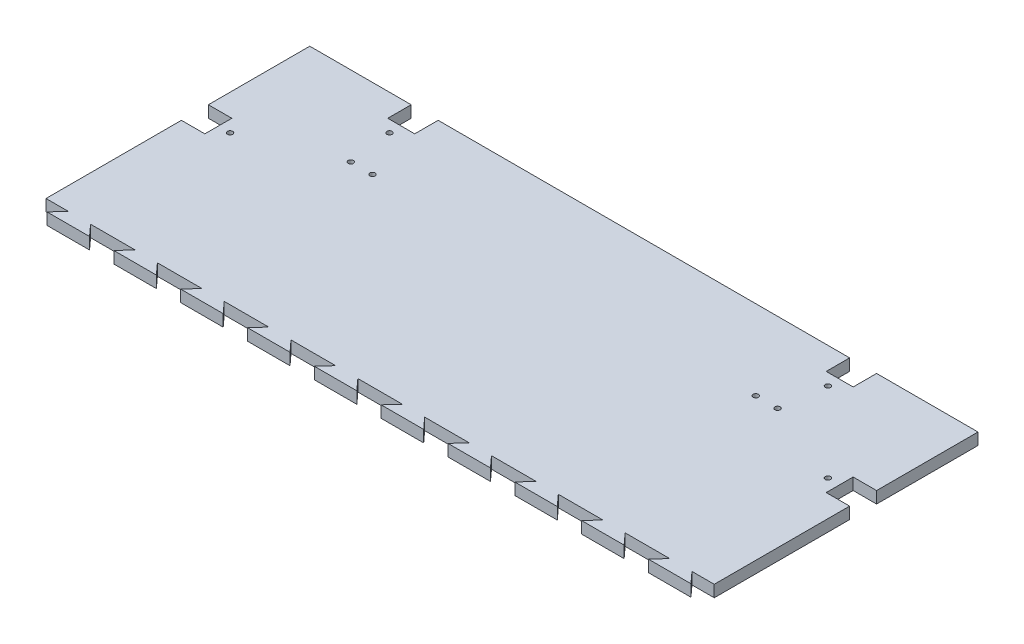
SolidWorks part; units mm, degrees
material "Multistrato di pioppo"
ref_plane "Piano frontale" through (0, 0, 0) normal (0, 0, 1) x (1, 0, 0)
ref_plane "Piano superiore" through (0, 0, 0) normal (0, 1, 0) x (1, 0, 0)
ref_plane "Piano destro" through (0, 0, 0) normal (1, 0, 0) x (0, 0, -1)
sketch "Schizzo1" plane through (0, 0, 0) normal (0, 1, 0) x (1, 0, 0)
  line L1 (0, 0) -> (-570, 0)
  line L2 (0, 0) -> (0, 450)
  line L3 (0, 450) -> (-570, 450)
  line L4 (-570, 0) -> (-570, 450)
  dimension "D1" = 570
  dimension "D2" = 450
extrude "Estrusione-Estrusione1" add sketch "Schizzo1" along normal blind 10
sketch "Schizzo2" plane through (0, 0, 0) normal (0, -1, 0) x (1, 0, 0)
  line L0 (-570, 0) -> (0, 0) construction
  line L1 (-483.5, 0) -> (-460.5, 0)
  line L3 (-483.5, 0) -> (-483.5, -20)
  line L5 (-483.5, -20) -> (-460.5, -20)
  line L6 (-460.5, 0) -> (-460.5, -20)
  line L7 (-483.5, 0) -> (-460.5, -20) construction
  line L8 (-483.5, -20) -> (-460.5, 0) construction
  line L9 (0, 0) -> (0, -450) construction
  line L10 (-109.5, 0) -> (-86.5, 0)
  line L11 (-109.5, 0) -> (-109.5, -20)
  line L12 (-109.5, -20) -> (-86.5, -20)
  line L13 (-86.5, 0) -> (-86.5, -20)
  line L14 (-109.5, 0) -> (-86.5, -20) construction
  line L15 (-109.5, -20) -> (-86.5, 0) construction
  line L16 (0, -86.5) -> (-20, -86.5)
  line L17 (0, -86.5) -> (0, -109.5)
  line L18 (0, -109.5) -> (-20, -109.5)
  line L19 (-20, -86.5) -> (-20, -109.5)
  line L20 (0, -86.5) -> (-20, -109.5) construction
  line L21 (0, -109.5) -> (-20, -86.5) construction
  line L22 (0, -450) -> (-570, -450) construction
  line L23 (0, -340.5) -> (-20, -340.5)
  line L24 (0, -340.5) -> (0, -363.5)
  line L25 (0, -363.5) -> (-20, -363.5)
  line L26 (-20, -340.5) -> (-20, -363.5)
  line L27 (0, -340.5) -> (-20, -363.5) construction
  line L28 (0, -363.5) -> (-20, -340.5) construction
  line L29 (-86.5, -450) -> (-109.5, -450)
  line L30 (-86.5, -450) -> (-86.5, -430)
  line L31 (-86.5, -430) -> (-109.5, -430)
  line L32 (-109.5, -450) -> (-109.5, -430)
  line L33 (-86.5, -450) -> (-109.5, -430) construction
  line L34 (-86.5, -430) -> (-109.5, -450) construction
  line L35 (-570, -450) -> (-570, 0) construction
  line L36 (-460.5, -450) -> (-483.5, -450)
  line L37 (-460.5, -450) -> (-460.5, -430)
  line L38 (-460.5, -430) -> (-483.5, -430)
  line L39 (-483.5, -450) -> (-483.5, -430)
  line L40 (-460.5, -450) -> (-483.5, -430) construction
  line L41 (-460.5, -430) -> (-483.5, -450) construction
  line L42 (-570, -363.5) -> (-550, -363.5)
  line L43 (-570, -363.5) -> (-570, -340.5)
  line L44 (-570, -340.5) -> (-550, -340.5)
  line L45 (-550, -363.5) -> (-550, -340.5)
  line L46 (-570, -363.5) -> (-550, -340.5) construction
  line L47 (-570, -340.5) -> (-550, -363.5) construction
  line L48 (-560, -98) -> (-10, -98) construction
  line L49 (-570, -109.5) -> (-550, -109.5)
  line L50 (-570, -109.5) -> (-570, -86.5)
  line L51 (-570, -86.5) -> (-550, -86.5)
  line L52 (-550, -109.5) -> (-550, -86.5)
  line L53 (-570, -109.5) -> (-550, -86.5) construction
  line L54 (-570, -86.5) -> (-550, -109.5) construction
  line L55 (-472, -10) -> (-472, -440) construction
  line L56 (-98, -440) -> (-98, -10) construction
  line L57 (-560, -352) -> (-10, -352) construction
  circle A2 centre (-467, -68) radius 2.25
  circle A3 centre (-448.5, -68) radius 2.25
  circle A6 centre (-121.5, -68) radius 2.25
  circle A7 centre (-103, -68) radius 2.25
  circle A8 centre (-467, -382) radius 2.25
  circle A9 centre (-448.5, -382) radius 2.25
  circle A14 centre (-121.5, -382) radius 2.25
  circle A15 centre (-103, -382) radius 2.25
  circle A16 centre (-472, -420) radius 2.25
  circle A17 centre (-540, -352) radius 2.25
  circle A18 centre (-540, -98) radius 2.25
  circle A19 centre (-472, -30) radius 2.25
  circle A20 centre (-98, -30) radius 2.25
  circle A21 centre (-30, -98) radius 2.25
  circle A22 centre (-30, -352) radius 2.25
  circle A23 centre (-98, -420) radius 2.25
  point P4 (-472, -10)
  point P17 (-98, -10)
  point P34 (-10, -98)
  point P41 (-10, -352)
  point P52 (-98, -440)
  point P59 (-472, -440)
  point P64 (-560, -352)
  point P71 (-560, -98)
  dimension "D1" = 4.5
  dimension "D3" = 98
  dimension "D5" = 98
  dimension "D2" = 98
  dimension "D4" = 98
  dimension "D6" = 23
  dimension "D7" = 20
extrude "Taglio-Estrusione1" cut sketch "Schizzo2" against normal blind 10
sketch "Schizzo3" plane through (0, 0, 0) normal (0, -1, 0) x (1, 0, 0)
  line L0 (-570, -225) -> (-551, -225)
  line L1 (-570, -340.5) -> (-570, -109.5) construction
  line L2 (-551, -225) -> (-560.1, -215) construction
  line L3 (-560.1, -215) -> (-522.9, -215) construction
  line L4 (-522.9, -215) -> (-532, -225) construction
  line L5 (-532, -225) -> (-513, -225)
  line L6 (-551, -225) -> (-532, -225) construction
  line L7 (-541.5, -225) -> (-541.5, -215) construction
  line L8 (-559.645, -215.5) -> (-523.355, -215.5)
  line L9 (-559.645, -215.5) -> (-551, -225)
  line L10 (-532, -225) -> (-523.355, -215.5)
  line L11 (-513, -225) -> (-494, -225)
  line L12 (-502.645, -215.5) -> (-494, -225)
  line L13 (-502.645, -215.5) -> (-466.355, -215.5)
  line L14 (-475, -225) -> (-466.355, -215.5)
  line L15 (-475, -225) -> (-456, -225)
  line L16 (-456, -225) -> (-437, -225)
  line L17 (-445.645, -215.5) -> (-437, -225)
  line L18 (-445.645, -215.5) -> (-409.355, -215.5)
  line L19 (-418, -225) -> (-409.355, -215.5)
  line L20 (-418, -225) -> (-399, -225)
  line L21 (-399, -225) -> (-380, -225)
  line L22 (-388.645, -215.5) -> (-380, -225)
  line L23 (-388.645, -215.5) -> (-352.355, -215.5)
  line L24 (-361, -225) -> (-352.355, -215.5)
  line L25 (-361, -225) -> (-342, -225)
  line L26 (-342, -225) -> (-323, -225)
  line L27 (-331.645, -215.5) -> (-323, -225)
  line L28 (-331.645, -215.5) -> (-295.355, -215.5)
  line L29 (-304, -225) -> (-295.355, -215.5)
  line L30 (-304, -225) -> (-285, -225)
  line L31 (-285, -225) -> (-266, -225)
  line L32 (-274.645, -215.5) -> (-266, -225)
  line L33 (-274.645, -215.5) -> (-238.355, -215.5)
  line L34 (-247, -225) -> (-238.355, -215.5)
  line L35 (-247, -225) -> (-228, -225)
  line L36 (-228, -225) -> (-209, -225)
  line L37 (-217.645, -215.5) -> (-209, -225)
  line L38 (-217.645, -215.5) -> (-181.355, -215.5)
  line L39 (-190, -225) -> (-181.355, -215.5)
  line L40 (-190, -225) -> (-171, -225)
  line L41 (-171, -225) -> (-152, -225)
  line L42 (-160.645, -215.5) -> (-152, -225)
  line L43 (-160.645, -215.5) -> (-124.355, -215.5)
  line L44 (-133, -225) -> (-124.355, -215.5)
  line L45 (-133, -225) -> (-114, -225)
  line L46 (-114, -225) -> (-95, -225)
  line L47 (-103.645, -215.5) -> (-95, -225)
  line L48 (-103.645, -215.5) -> (-67.355, -215.5)
  line L49 (-76, -225) -> (-67.355, -215.5)
  line L50 (-76, -225) -> (-57, -225)
  line L51 (-57, -225) -> (-38, -225)
  line L52 (-46.645, -215.5) -> (-38, -225)
  line L53 (-46.645, -215.5) -> (-10.355, -215.5)
  line L54 (-19, -225) -> (-10.355, -215.5)
  line L55 (-19, -225) -> (0, -225)
  line L56 (0, -109.5) -> (0, -340.5) construction
  line L57 (-570, -225) -> (-570, 0)
  line L58 (-570, 0) -> (0, 0)
  line L59 (0, 0) -> (0, -225)
  dimension "D1" = 57
  dimension "D2" = 10
  dimension "D3" = 37.2
  dimension "D4" = 19
  dimension "D5" = 0.5
  dimension "D6" = 10
extrude "Taglio-Estrusione2" cut sketch "Schizzo3" against normal blind 10
